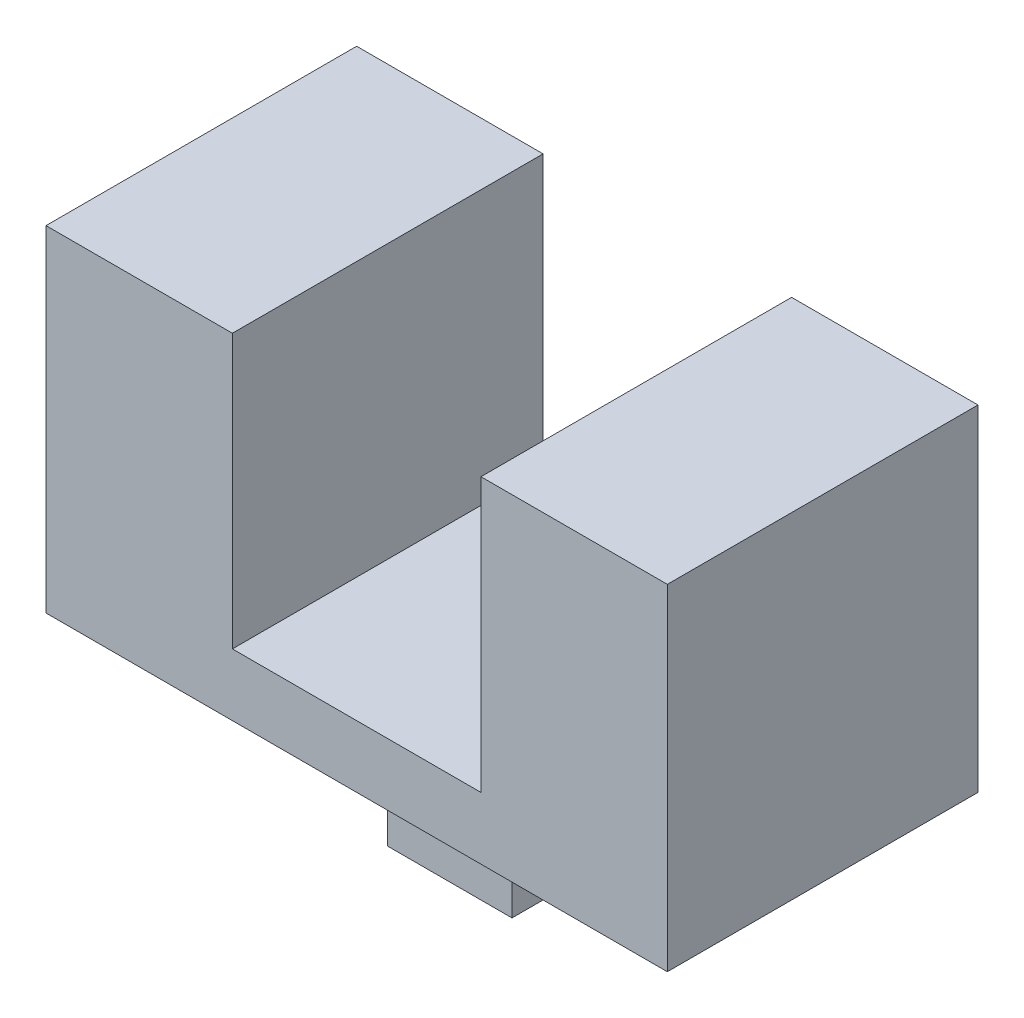
SolidWorks part; units mm, degrees
ref_plane "Front Plane" through (0, 0, 0) normal (0, 0, 1) x (1, 0, 0)
ref_plane "Top Plane" through (0, 0, 0) normal (0, 1, 0) x (1, 0, 0)
ref_plane "Right Plane" through (0, 0, 0) normal (1, 0, 0) x (0, 0, -1)
sketch "Sketch1" plane through (0, 0, 0) normal (0, 0, 1) x (1, 0, 0)
  line L0 (0, 0) -> (0, 11.8596) construction
  line L1 (6.35, -3.429) -> (-6.35, -3.429)
  line L2 (6.35, -3.429) -> (6.35, 3.429)
  line L3 (6.35, 3.429) -> (2.54, 3.429)
  line L4 (-6.35, -3.429) -> (-6.35, 3.429)
  line L5 (6.35, -3.429) -> (-6.35, 3.429) construction
  line L6 (6.35, 3.429) -> (-6.35, -3.429) construction
  line L7 (-2.54, 3.429) -> (-6.35, 3.429)
  line L8 (2.54, -2.159) -> (-2.54, -2.159)
  line L9 (2.54, -2.159) -> (2.54, 3.429)
  line L11 (-2.54, -2.159) -> (-2.54, 3.429)
  line L12 (2.54, -2.159) -> (-2.54, 3.429) construction
  line L13 (2.54, 3.429) -> (-2.54, -2.159) construction
  point P0 (0, 0)
  point P8 (0, 0.635)
  dimension "D1" = 12.7
  dimension "D2" = 6.858
  dimension "D3" = 5.08
  dimension "D4" = 5.588
extrude "Boss-Extrude1" add sketch "Sketch1" along normal blind 6.35
sketch "Sketch2" plane through (0, -3.429, 0) normal (0, -1, 0) x (1, 0, 0)
  line L0 (-6.35, 6.35) -> (6.35, 0) construction
  line L2 (-1.27, 1.905) -> (1.27, 1.905)
  line L3 (-1.27, 1.905) -> (-1.27, 4.445)
  line L4 (-1.27, 4.445) -> (1.27, 4.445)
  line L5 (1.27, 1.905) -> (1.27, 4.445)
  line L6 (-1.27, 1.905) -> (1.27, 4.445) construction
  line L7 (-1.27, 4.445) -> (1.27, 1.905) construction
  point P4 (0, 3.175)
  dimension "D1" = 2.54
  dimension "D2" = 2.54
extrude "Boss-Extrude2" add sketch "Sketch2" along normal blind 2.54
